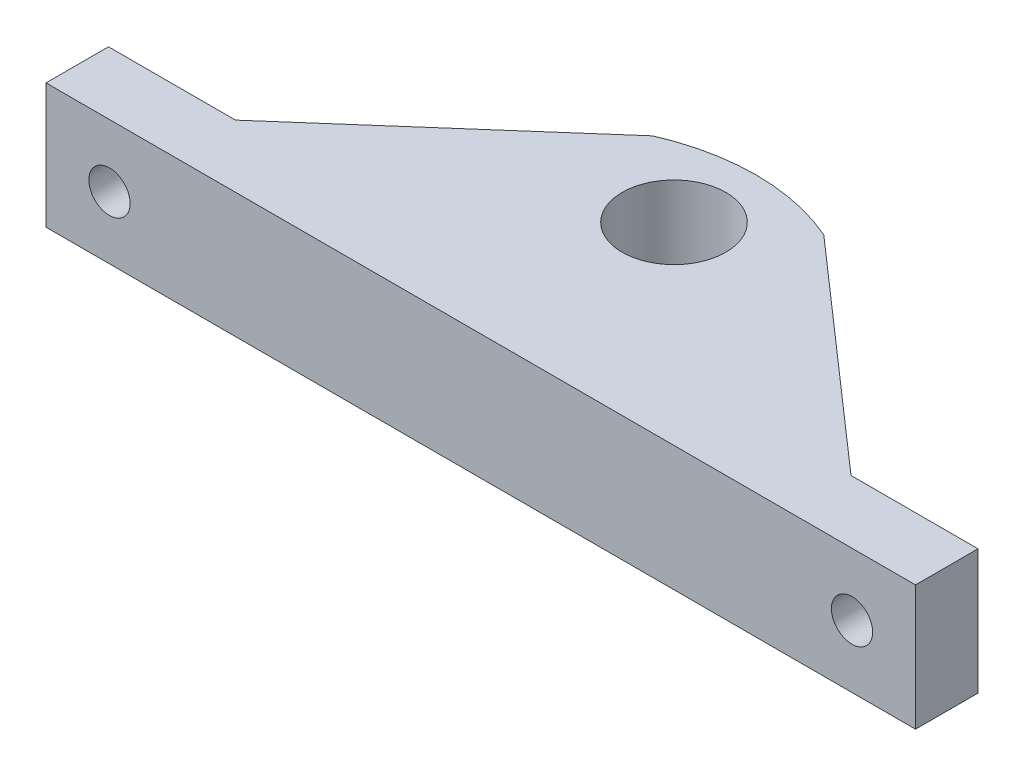
SolidWorks part; units mm, degrees
ref_plane "Piano frontale" through (0, 0, 0) normal (0, 0, 1) x (1, 0, 0)
ref_plane "Piano superiore" through (0, 0, 0) normal (0, 1, 0) x (1, 0, 0)
ref_plane "Piano destro" through (0, 0, 0) normal (1, 0, 0) x (0, 0, -1)
sketch "Schizzo1" plane through (0, 0, 0) normal (0, 0, 1) x (1, 0, 0)
  line L1 (-34.78, 5) -> (34.78, 5)
  line L2 (-34.78, 5) -> (-34.78, -5)
  line L3 (-34.78, -5) -> (34.78, -5)
  line L4 (34.78, 5) -> (34.78, -5)
  line L5 (-34.78, 5) -> (34.78, -5) construction
  line L6 (-34.78, -5) -> (34.78, 5) construction
  point P0 (0, 0)
  dimension "D1" = 69.56
  dimension "D2" = 10
extrude "Estrusione-Estrusione1" add sketch "Schizzo1" along normal blind 5
sketch "Schizzo2" plane through (0, -5, 0) normal (0, -1, 0) x (1, 0, 0)
  line L1 (0, 0) -> (0, -27.1852) construction
  line L2 (24.6213, 0) -> (-24.6213, 0)
  line L4 (6.8575, -15.5842) -> (24.6213, 0)
  line L5 (-6.8575, -15.5842) -> (-24.6213, 0)
  arc A0 (-6.8575, -15.5842) -> (6.8575, -15.5842) centre (0, 0) ccw
  circle A1 centre (0, -10.4602) radius 4.15
  dimension "D1" = 8.3
extrude "Estrusione-Estrusione2" add sketch "Schizzo2" against normal up to surface (10 mm away) up to face at (0, 5, 2.5)
sketch "Schizzo3" plane through (0, 0, 0) normal (0, 0, -1) x (-1, 0, 0)
  line L0 (-34.78, 5) -> (-24.6213, -5) construction
  circle A0 centre (-29.7006, 0) radius 1.65
  dimension "D1" = 3.3
extrude "Taglio-Estrusione1" cut sketch "Schizzo3" against normal blind 5 contours A0
mirror "Specchia1" about plane through (0, 0, 0) normal (1, 0, 0) of "Taglio-Estrusione1"
